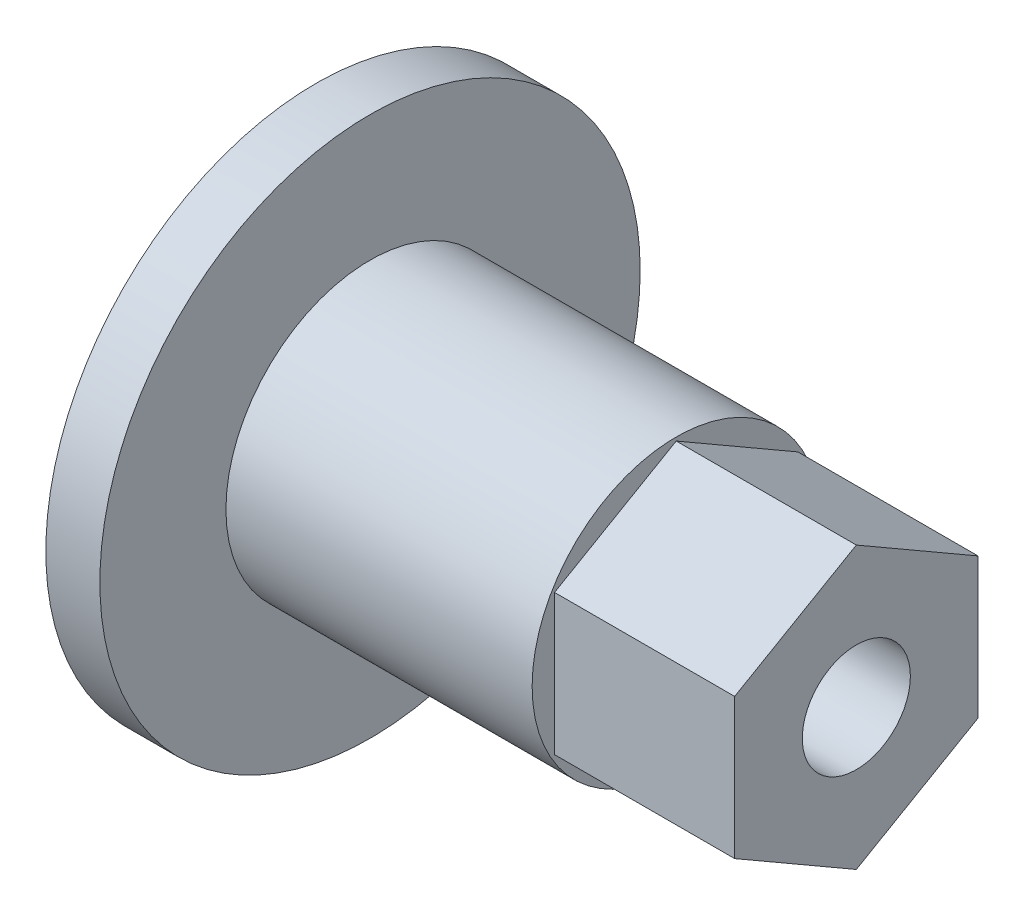
SolidWorks part; units mm, degrees
ref_plane "Front Plane" through (0, 0, 0) normal (0, 0, 1) x (1, 0, 0)
ref_plane "Top Plane" through (0, 0, 0) normal (0, 1, 0) x (1, 0, 0)
ref_plane "Right Plane" through (0, 0, 0) normal (1, 0, 0) x (0, 0, -1)
sketch "Sketch1" plane through (0, 0, 0) normal (0, 1, 0) x (1, 0, 0)
  line L1 (1.5, 4) -> (15, 4)
  line L3 (0, 0) -> (0, 7.5)
  line L4 (15, 4) -> (15, 0)
  line L5 (15, 0) -> (0, 0)
  line L6 (0, 7.5) -> (1.5, 7.5)
  line L7 (1.5, 7.5) -> (1.5, 4)
  dimension "D1" = 4
  dimension "D2" = 13.5
  dimension "D3" = 1.5
  dimension "D4" = 7.5
revolve "Revolve1" add sketch "Sketch1" angle 360 about L5
sketch "Sketch2" plane through (15, 0, 0) normal (1, 0, 0) x (0, 0, -1)
  line L1 (0, 3.9) -> (-3.3775, 1.95)
  line L2 (-3.3775, 1.95) -> (-3.3775, -1.95)
  line L3 (-3.3775, -1.95) -> (0, -3.9)
  line L4 (0, -3.9) -> (3.3775, -1.95)
  line L5 (3.3775, -1.95) -> (3.3775, 1.95)
  line L6 (3.3775, 1.95) -> (0, 3.9)
  circle A1 centre (0, 0) radius 3.3775 construction
  dimension "D1" = 3.9
extrude "Cut-Extrude1" cut sketch "Sketch2" against normal blind 5 flip side to cut
hole_wizard "M3x0.5 Tapped Hole4" positions "Sketch5" profile "Sketch6" tap size "M3x0.5" standard "ANSI Metric"
sketch "Sketch5" plane through (15, 0, 0) normal (1, 0, 0) x (0, 0, -1)
  point P0 (0, 0)
sketch "Sketch6" plane through (15, 0, 0) normal (0, 1, 0) x (0, 0, -1)
  line L0 (0, 0) -> (0, 9.2511)
  line L1 (0, 9.2511) -> (1.25, 8.5)
  line L2 (1.25, 8.5) -> (1.25, 6)
  line L3 (1.25, 6) -> (1.5, 6)
  line L4 (1.5, 6) -> (1.5, 0)
  line L5 (1.5, 0) -> (0, 0)
  line L10 (0, 9.2511) -> (-1.25, 8.5) construction
  line L11 (0, -6.35) -> (0, 107.95) construction
  dimension "Tap Drill Dia." = 2.5
  dimension "Tap Drill Depth" = 8.5
  dimension "Thread Major Dia." = 3
  dimension "Thread Depth" = 6
  dimension "Drill Angle" = 118
sketch "Sketch7" plane through (0, 0, 0) normal (-1, 0, 0) x (0, 0, 1)
  circle A0 centre (0, 0) radius 1.585
extrude "Cut-Extrude2" cut sketch "Sketch7" against normal blind 6.35
